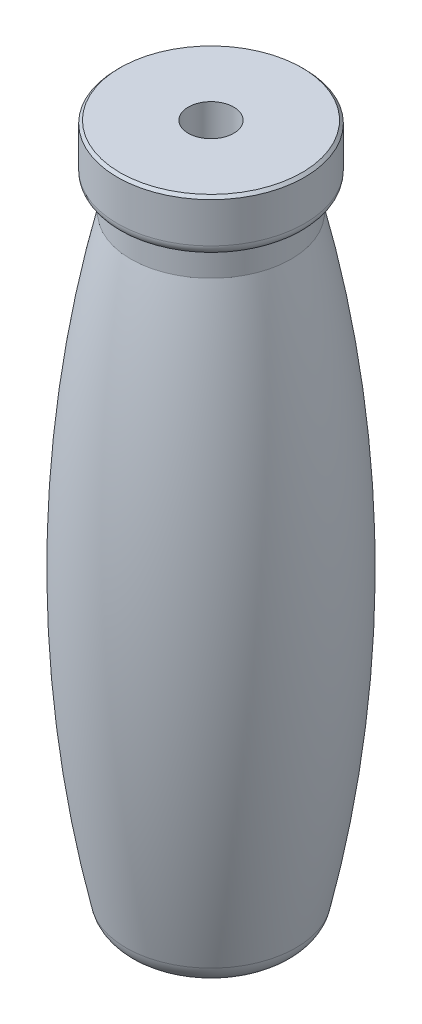
SolidWorks part; units mm, degrees
ref_plane "Front Plane" through (0, 0, 0) normal (0, 0, 1) x (1, 0, 0)
ref_plane "Top Plane" through (0, 0, 0) normal (0, 1, 0) x (1, 0, 0)
ref_plane "Right Plane" through (0, 0, 0) normal (1, 0, 0) x (0, 0, -1)
sketch "Sketch1" plane through (0, 0, 0) normal (0, 1, 0) x (1, 0, 0)
  circle A0 centre (0, 0) radius 17.5
  dimension "D1" = 35
extrude "Boss-Extrude1" add sketch "Sketch1" along normal blind 10
sketch "Sketch2" plane through (0, 0, 0) normal (1, 0, 0) x (0, 0, -1)
  line L0 (0, 0) -> (0, -120) construction
  line L1 (15, 0) -> (15, -5)
  line L3 (0, -120) -> (15, -120)
  line L4 (15, 0) -> (0, 0)
  line L5 (0, 0) -> (0, -120)
  arc A0 (15, -120) -> (15, -5) centre (-228.2977, -62.5) ccw
  dimension "D5" = 250
  dimension "D1" = 5
  dimension "D2" = 120
  dimension "D3" = 15
  dimension "D4" = 15
revolve "Revolve1" add sketch "Sketch2" angle 360 about L0
fillet "Fillet1" radius 5 1 edges at (0, -120, 15)
sketch "Sketch3" plane through (0, -120, 0) normal (0, -1, 0) x (1, 0, 0)
  circle A0 centre (0, 0) radius 7.5
  dimension "D1" = 15
extrude "Cut-Extrude1" cut sketch "Sketch3" against normal blind 110
sketch "Sketch4" plane through (0, 10, 0) normal (0, 1, 0) x (1, 0, 0)
  circle A0 centre (0, 0) radius 4.25
  dimension "D1" = 8.5
extrude "Cut-Extrude2" cut sketch "Sketch4" against normal blind 20
fillet "Fillet5" radius 2 1 edges at (0, 0, 17.5)
chamfer "Chamfer1" distance 0.5 angle 45 1 edges at (0, 10, 17.5)
